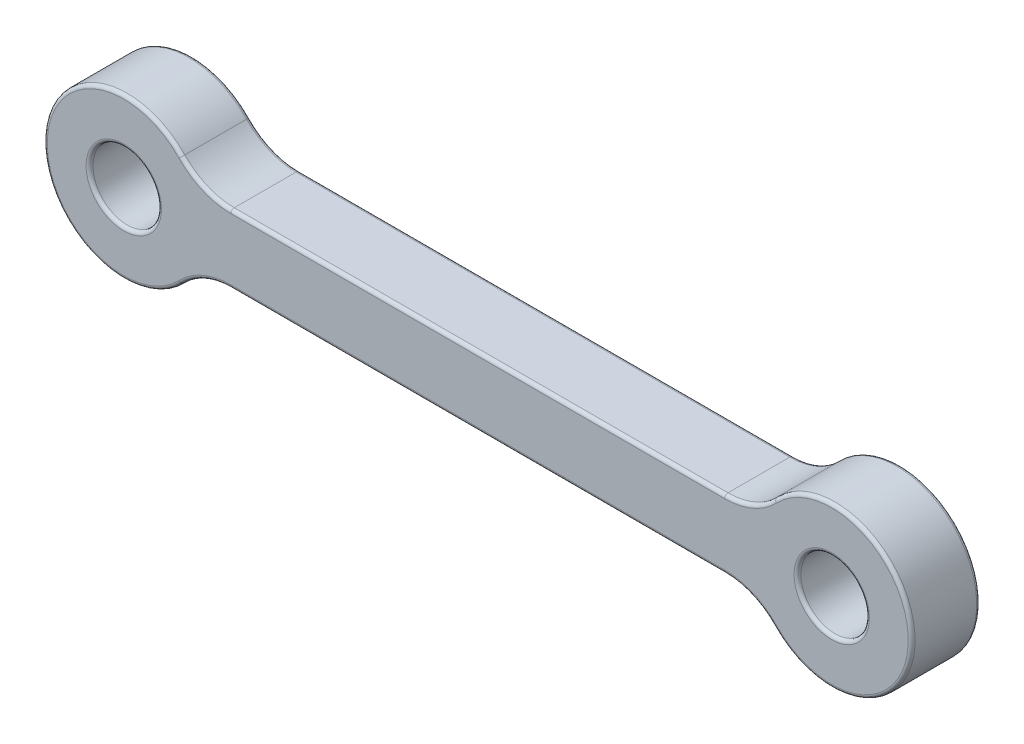
SolidWorks part; units mm, degrees
ref_plane "Front Plane" through (0, 0, 0) normal (0, 0, 1) x (1, 0, 0)
ref_plane "Top Plane" through (0, 0, 0) normal (0, 1, 0) x (1, 0, 0)
ref_plane "Right Plane" through (0, 0, 0) normal (1, 0, 0) x (0, 0, -1)
sketch "Sketch1" plane through (0, 0, 0) normal (0, 0, 1) x (1, 0, 0)
  line L0 (0, 0) -> (31, 0) construction
  line L1 (0, 3.5) -> (31, 3.5) construction
  line L2 (0, -3.5) -> (31, -3.5) construction
  line L3 (15.5, 0) -> (15.5, -3.5) construction
  line L5 (27.8377, -1.5) -> (3.1623, -1.5)
  line L6 (27.8377, -1.5) -> (27.8377, 1.5) construction
  line L7 (27.8377, 1.5) -> (3.1623, 1.5)
  line L8 (3.1623, -1.5) -> (3.1623, 1.5) construction
  line L9 (27.8377, -1.5) -> (3.1623, 1.5) construction
  line L10 (27.8377, 1.5) -> (3.1623, -1.5) construction
  arc A0 (0, 3.5) -> (0, -3.5) centre (0, 0) ccw construction
  arc A1 (31, -3.5) -> (31, 3.5) centre (31, 0) ccw construction
  circle A2 centre (0, 0) radius 1.5
  circle A3 centre (0, 0) radius 3.5
  circle A4 centre (31, 0) radius 1.5
  circle A5 centre (31, 0) radius 3.5
  point P3 (15.5, 0)
  dimension "D3" = 3
  dimension "D1" = 31
  dimension "D2" = 7
  dimension "D4" = 3
extrude "Boss-Extrude1" add sketch "Sketch1" along normal mid plane 3 contours A3 A2 | A5 A4 | L5 A5 L7 A3
fillet "Fillet1" radius 3 4 edges at (3.1623, -1.5, 0) (27.8377, -1.5, 0) (27.8377, 1.5, 0) (3.1623, 1.5, 0)
fillet "Fillet2" radius 0.15 20 edges at (32.5, 0, -1.5) (3.5137, -1.7404, -1.5) (15.5, -1.5, -1.5) (27.4863, -1.7404, -1.5) (34.5, 0, -1.5) (27.4863, 1.7404, -1.5) (15.5, 1.5, -1.5) (3.5137, 1.7404, -1.5) (-3.5, 0, -1.5) (1.5, 0, -1.5) (32.5, 0, 1.5) (27.4863, 1.7404, 1.5) (34.5, 0, 1.5) (27.4863, -1.7404, 1.5) (15.5, -1.5, 1.5) (3.5137, -1.7404, 1.5) (-3.5, 0, 1.5) (3.5137, 1.7404, 1.5) (15.5, 1.5, 1.5) (1.5, 0, 1.5)
